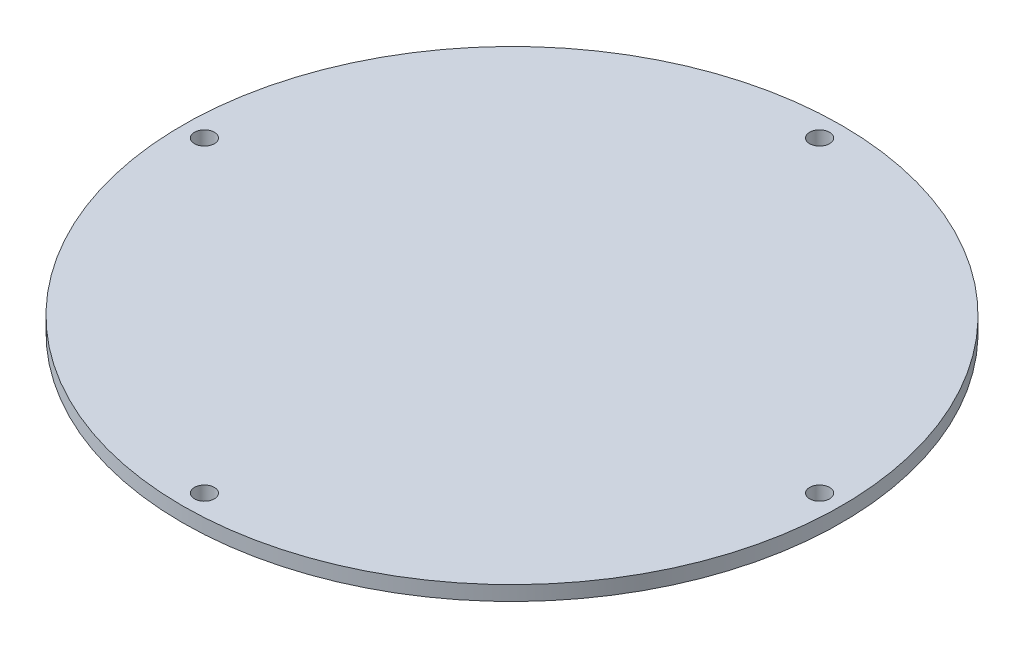
SolidWorks part; units mm, degrees
ref_plane "Front Plane" through (0, 0, 0) normal (0, 0, 1) x (1, 0, 0)
ref_plane "Top Plane" through (0, 0, 0) normal (0, 1, 0) x (1, 0, 0)
ref_plane "Right Plane" through (0, 0, 0) normal (1, 0, 0) x (0, 0, -1)
sketch "Sketch1" plane through (0, 0, 0) normal (0, 1, 0) x (1, 0, 0)
  circle A0 centre (0, 0) radius 57.15
  dimension "D1" = 114.3
extrude "Boss-Extrude1" add sketch "Sketch1" along normal blind 2.54
sketch "Sketch2" plane through (0, 2.54, 0) normal (0, 1, 0) x (1, 0, 0)
  circle A2 centre (0, 0) radius 57.15 construction
  point P0 (-53.34, 0)
  dimension "D1" = 53.34
sketch "Sketch5" plane through (0, 2.54, 0) normal (0, 1, 0) x (1, 0, 0)
  point P0 (-53.34, 0)
hole_wizard "#8-32 Tapped Hole1" positions "Sketch5" profile "Sketch6" tap size "#8-32" standard "ANSI Inch" end condition through all
sketch "Sketch6" plane through (-53.34, 2.54, 0) normal (1, 0, 0) x (0, 0, 1)
  line L0 (0, 0) -> (0, 2.54)
  line L1 (0, 2.54) -> (1.7272, 2.54)
  line L2 (1.7272, 2.54) -> (1.7272, 0)
  line L5 (1.7272, 0) -> (0, 0)
  line L11 (0, -6.35) -> (0, 107.95) construction
  dimension "Thru Tap Drill Dia." = 3.4544
  dimension "Thru Tap Drill Depth" = 2.54
cosmetic thread "Hole Thread5" parameters "D2"=4.1656
pattern_circular "CirPattern2" count 4 over 360 about axis through (0, 0, 0) along (0, 1, 0) of "#8-32 Tapped Hole1"
cosmetic thread "Hole Thread6" parameters "D2"=4.1656
cosmetic thread "Hole Thread7" parameters "D2"=4.1656
cosmetic thread "Hole Thread8" parameters "D2"=4.1656
